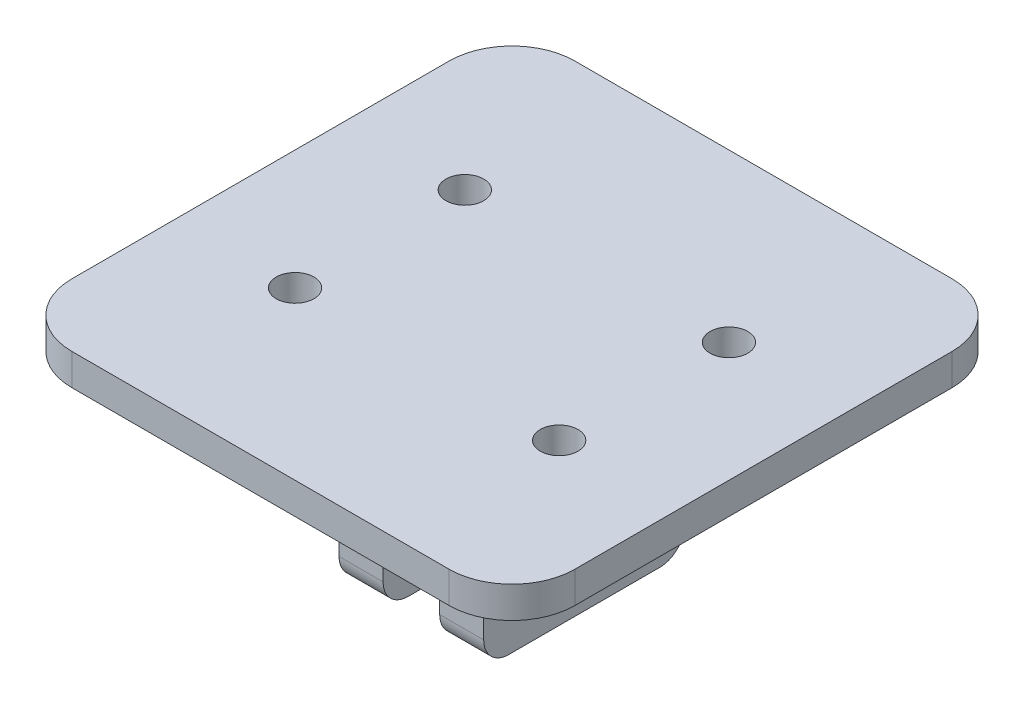
SolidWorks part; units mm, degrees
ref_plane "Front Plane" through (0, 0, 0) normal (0, 0, 1) x (1, 0, 0)
ref_plane "Top Plane" through (0, 0, 0) normal (0, 1, 0) x (1, 0, 0)
ref_plane "Right Plane" through (0, 0, 0) normal (1, 0, 0) x (0, 0, -1)
sketch "Sketch1" plane through (0, 0, 0) normal (0, 1, 0) x (1, 0, 0)
  line L0 (10.5, 0) -> (-10.5, 0) construction
  line L1 (15, 20) -> (-15, 20)
  line L2 (20, 15) -> (20, -15)
  line L3 (15, -20) -> (-15, -20)
  line L4 (-20, 15) -> (-20, -15)
  line L5 (20, 20) -> (-20, -20) construction
  line L6 (20, -20) -> (-20, 20) construction
  line L7 (0, -10.5) -> (0, 10.5) construction
  line L8 (0, 6.75) -> (0, -6.75)
  line L9 (10.5, 10.5) -> (-10.5, 10.5) construction
  line L10 (10.5, 10.5) -> (10.5, -10.5) construction
  line L11 (10.5, -10.5) -> (-10.5, -10.5) construction
  line L12 (-10.5, 10.5) -> (-10.5, -10.5) construction
  line L13 (10.5, 10.5) -> (-10.5, -10.5) construction
  line L14 (10.5, -10.5) -> (-10.5, 10.5) construction
  arc A4 (15, 20) -> (20, 15) centre (15, 15) cw
  arc A5 (20, -15) -> (15, -20) centre (15, -15) cw
  arc A6 (-15, -20) -> (-20, -15) centre (-15, -15) cw
  arc A7 (-15, 20) -> (-20, 15) centre (-15, 15) ccw
  circle A8 centre (10.5, -6.75) radius 1.5
  circle A9 centre (-10.5, -6.75) radius 1.5
  circle A10 centre (-10.5, 6.75) radius 1.5
  circle A11 centre (10.5, 6.75) radius 1.5
  point P0 (0, 0)
  point P6 (0, 0)
  point P9 (0, 0)
  point P12 (0, 0)
  point P17 (0, 0)
  point P18 (0, 0)
  point P19 (0, 0)
  point P40 (0, 0)
  dimension "D5" = 3
  dimension "D6" = 3
  dimension "D7" = 3
  dimension "D8" = 3
  dimension "D9" = 5
  dimension "D1" = 40
  dimension "D2" = 40
  dimension "D3" = 21
  dimension "D4" = 21
  dimension "D10" = 21
  dimension "D11" = 13.5
extrude "Boss-Extrude1" add sketch "Sketch1" along normal blind 2.5
sketch "Sketch2" plane through (0, 0, 0) normal (0, -1, 0) x (1, 0, 0)
  line L0 (0, 19.0027) -> (0, -17.8614) construction
  line L1 (4, 0) -> (-4, 0) construction
  line L2 (2.25, -8) -> (5.75, 8) construction
  line L3 (-2.25, 8) -> (-5.75, 8)
  line L4 (-2.25, 8) -> (-2.25, -8)
  line L5 (-2.25, -8) -> (-5.75, -8)
  line L6 (-5.75, 8) -> (-5.75, -8)
  line L7 (-2.25, 8) -> (-5.75, -8) construction
  line L8 (-2.25, -8) -> (-5.75, 8) construction
  line L9 (2.25, 8) -> (5.75, -8) construction
  line L10 (5.75, 8) -> (5.75, -8)
  line L11 (2.25, -8) -> (5.75, -8)
  line L12 (2.25, 8) -> (2.25, -8)
  line L13 (2.25, 8) -> (5.75, 8)
  point P6 (0, 0)
  dimension "D1" = 8
  dimension "D2" = 3.5
  dimension "D3" = 3.5
  dimension "D4" = 16
extrude "Boss-Extrude2" add sketch "Sketch2" along normal blind 15
fillet "Fillet1" radius 2 4 edges at (4, -15, 8) (-4, -15, 8) (4, -15, -8) (-4, -15, -8)
sketch "Sketch3" plane through (-5.75, 0, 0) normal (-1, 0, 0) x (0, 0, 1)
  line L0 (0, -15) -> (0, -6.7657) construction
  line L1 (-6, -15) -> (6, -15) construction
  circle A0 centre (0, -10) radius 3
  dimension "D1" = 6
  dimension "D2" = 5
extrude "Cut-Extrude1" cut sketch "Sketch3" against normal through all both and the other way through all
